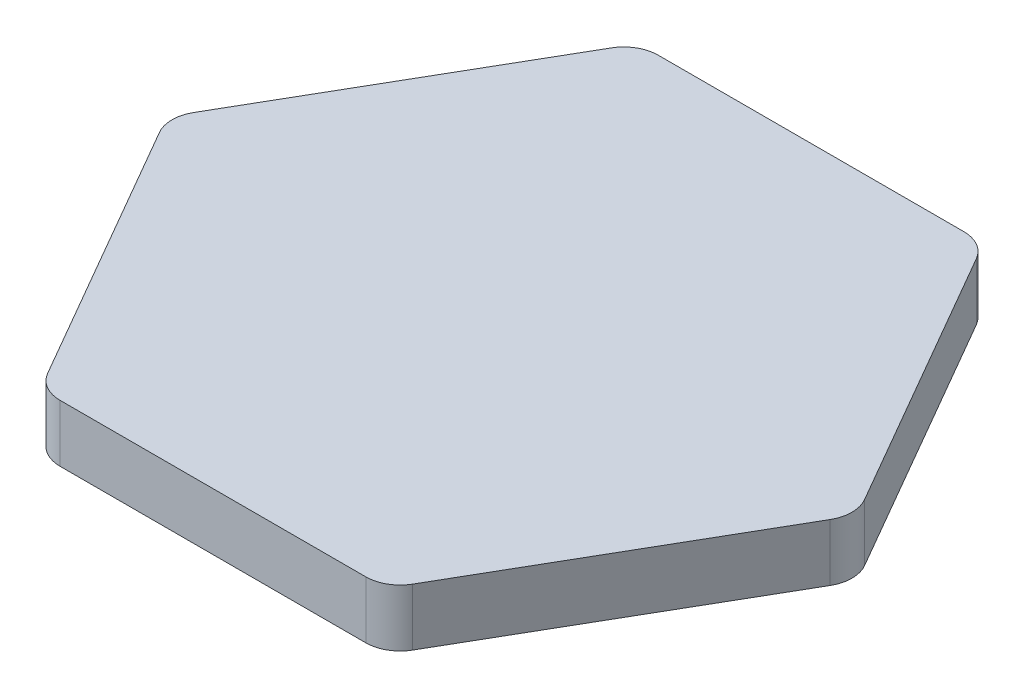
SolidWorks part; units mm, degrees
ref_plane "Front Plane" through (0, 0, 0) normal (0, 0, 1) x (1, 0, 0)
ref_plane "Top Plane" through (0, 0, 0) normal (0, 1, 0) x (1, 0, 0)
ref_plane "Right Plane" through (0, 0, 0) normal (1, 0, 0) x (0, 0, -1)
sketch "Sketch1" plane through (0, 0, 0) normal (0, 1, 0) x (1, 0, 0)
  line L1 (-30.2002, 0) -> (-15.1001, -26.1542)
  line L2 (-15.1001, -26.1542) -> (15.1001, -26.1542)
  line L3 (15.1001, -26.1542) -> (30.2002, 0)
  line L4 (30.2002, 0) -> (15.1001, 26.1542)
  line L5 (15.1001, 26.1542) -> (-15.1001, 26.1542)
  line L6 (-15.1001, 26.1542) -> (-30.2002, 0)
  circle A0 centre (0, 0) radius 26.1542 construction
extrude "Boss-Extrude1" add sketch "Sketch1" along normal blind 5
fillet "Fillet1" radius 3 6 edges at (-30.2002, 2.5, 0) (-15.1001, 2.5, -26.1542) (15.1001, 2.5, -26.1542) (30.2002, 2.5, 0) (15.1001, 2.5, 26.1542) (-15.1001, 2.5, 26.1542)
